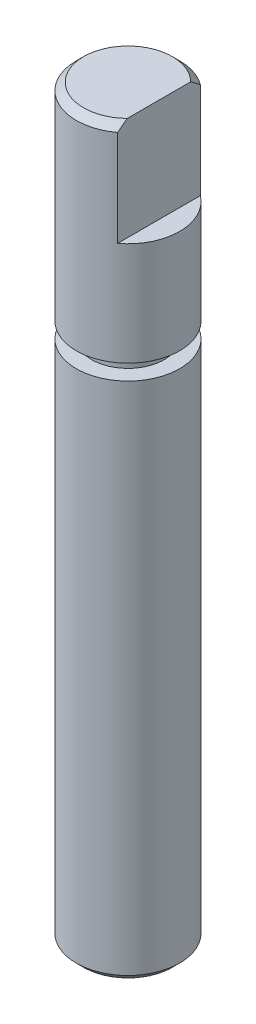
SolidWorks part; units mm, degrees
ref_plane "Plan de face" through (0, 0, 0) normal (0, 0, 1) x (1, 0, 0)
ref_plane "Plan de dessus" through (0, 0, 0) normal (0, 1, 0) x (1, 0, 0)
ref_plane "Plan de droite" through (0, 0, 0) normal (1, 0, 0) x (0, 0, -1)
sketch "Esquisse1" plane through (0, 0, 0) normal (0, 0, 1) x (1, 0, 0)
  line L0 (0, 0) -> (-4.2929, 0)
  line L1 (-4.2929, 0) -> (-5, 0.7071)
  line L2 (-5, 0.7071) -> (-5, 50.5)
  line L3 (-5, 50.5) -> (-3.5, 50.5)
  line L4 (-3.5, 50.5) -> (-3.5, 52)
  line L5 (-3.5, 52) -> (-5, 52)
  line L6 (-5, 52) -> (-5, 71.2929)
  line L7 (-5, 71.2929) -> (-4.2929, 72)
  line L8 (-4.2929, 72) -> (0, 72)
  line L9 (0, 72) -> (0, 0)
  dimension "D1" = 72
  dimension "D2" = 5
  dimension "D3" = 5
  dimension "D4" = 135
  dimension "D5" = 20
  dimension "D6" = 1.5
  dimension "D7" = 1
  dimension "D8" = 1
  dimension "D9" = 1.5
revolve "Révolution1" add sketch "Esquisse1" angle 360 about L9
sketch "Esquisse2" plane through (0, 0, 0) normal (0, 0, 1) x (1, 0, 0)
  line L0 (5, 52) -> (5, 71.2929) construction
  line L1 (9, 76) -> (3, 76)
  line L2 (9, 76) -> (9, 62)
  line L3 (9, 62) -> (3, 62)
  line L4 (3, 76) -> (3, 62)
  line L5 (4.2929, 72) -> (-4.2929, 72) construction
  dimension "D1" = 2
  dimension "D2" = 10
  dimension "D3" = 14
  dimension "D4" = 6
extrude "Enlèv. mat.-Extru.1" cut sketch "Esquisse2" against normal through all and the other way through all
